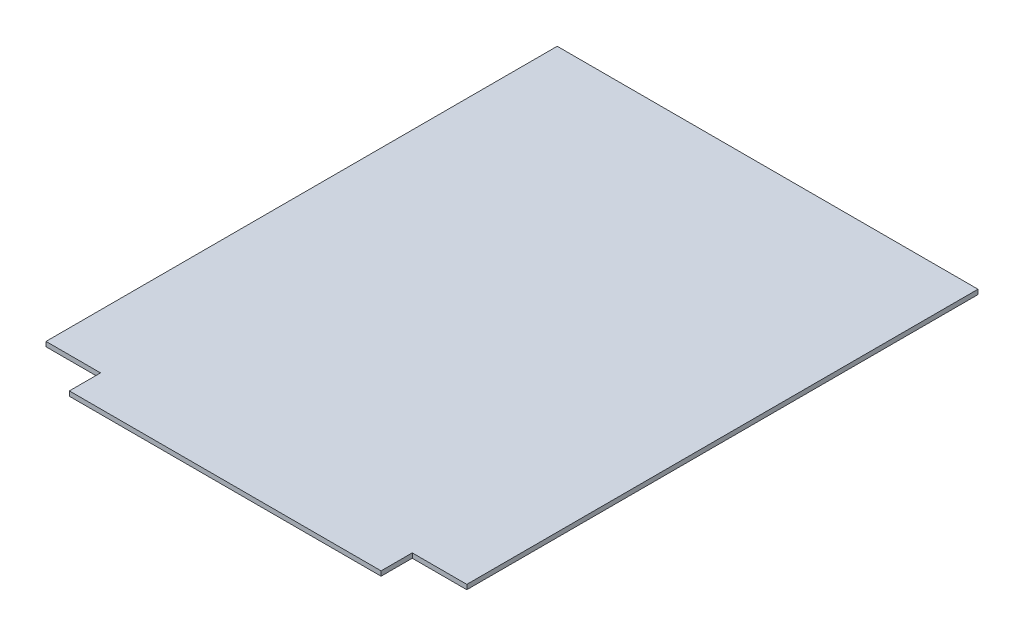
SolidWorks part; units mm, degrees
ref_plane "Front Plane" through (0, 0, 0) normal (0, 0, 1) x (1, 0, 0)
ref_plane "Top Plane" through (0, 0, 0) normal (0, 1, 0) x (1, 0, 0)
ref_plane "Right Plane" through (0, 0, 0) normal (1, 0, 0) x (0, 0, -1)
sketch "Sketch1" plane through (0, 0, 0) normal (0, 1, 0) x (1, 0, 0)
  line L1 (-135, -164) -> (135, -164)
  line L2 (-135, -164) -> (-135, 164)
  line L3 (-135, 164) -> (135, 164)
  line L4 (135, -164) -> (135, 164)
  line L5 (-135, -164) -> (135, 164) construction
  line L6 (-135, 164) -> (135, -164) construction
  line L7 (-100, -164) -> (100, -164)
  line L8 (-100, -164) -> (-100, -184)
  line L9 (-100, -184) -> (100, -184)
  line L10 (100, -164) -> (100, -184)
  point P0 (0, 0)
  dimension "D1" = 270
  dimension "D2" = 328
  dimension "D3" = 200
  dimension "D4" = 35
  dimension "D5" = 35
  dimension "D6" = 20
extrude "Boss-Extrude1" add sketch "Sketch1" along normal blind 3 contours L10 L1 L8 L9 | L1 L4 L3 L2
